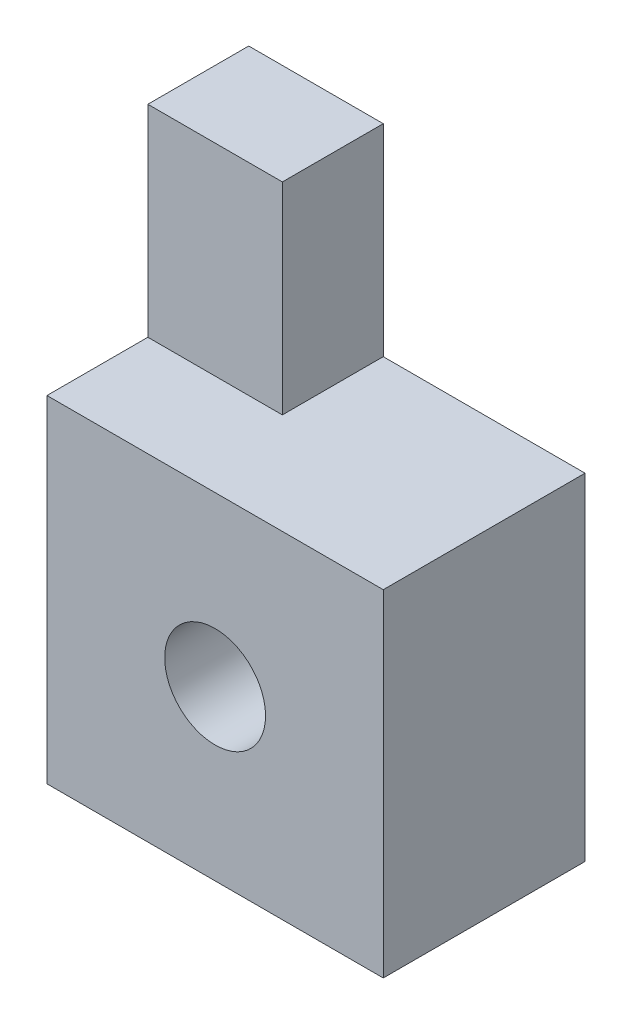
SolidWorks part; units mm, degrees
ref_plane "Front Plane" through (0, 0, 0) normal (0, 0, 1) x (1, 0, 0)
ref_plane "Top Plane" through (0, 0, 0) normal (0, 1, 0) x (1, 0, 0)
ref_plane "Right Plane" through (0, 0, 0) normal (1, 0, 0) x (0, 0, -1)
sketch "Sketch1" plane through (0, 0, 0) normal (0, 0, 1) x (1, 0, 0)
  line L1 (25, 25) -> (-25, 25)
  line L2 (25, 25) -> (25, -25)
  line L3 (25, -25) -> (-25, -25)
  line L4 (-25, 25) -> (-25, -25)
  line L5 (25, 25) -> (-25, -25) construction
  line L6 (25, -25) -> (-25, 25) construction
  point P0 (0, 0)
  dimension "D1" = 50
  dimension "D2" = 50
extrude "Boss-Extrude1" add sketch "Sketch1" along normal blind 30
sketch "Sketch2" plane through (0, 0, 30) normal (0, 0, 1) x (1, 0, 0)
  circle A0 centre (0, 0) radius 7.5
  dimension "D1" = 15
extrude "Cut-Extrude1" cut sketch "Sketch2" against normal up to next
sketch "Sketch4" plane through (0, 25, 0) normal (0, 1, 0) x (1, 0, 0)
  line L1 (-25, 0) -> (-5, 0)
  line L2 (-25, 0) -> (-25, -15)
  line L3 (-25, -15) -> (-5, -15)
  line L5 (-5, 0) -> (-5, -15)
  dimension "D1" = 20
extrude "Boss-Extrude3" add sketch "Sketch4" along normal blind 30
